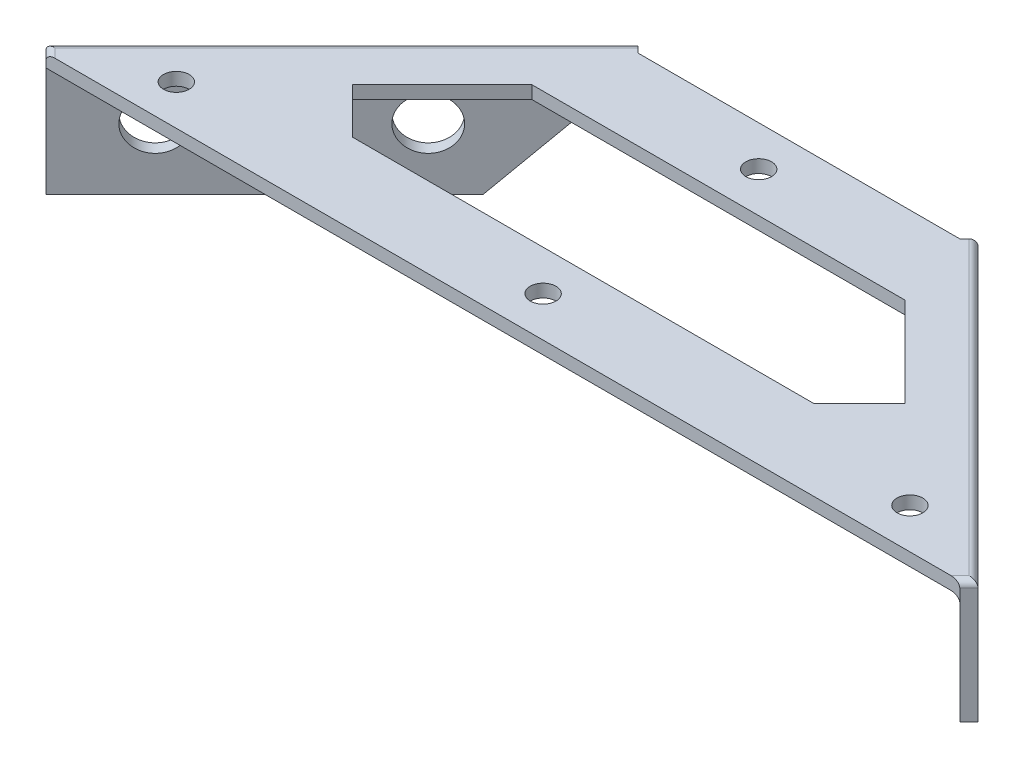
SolidWorks part; units mm, degrees
material "1060 Alloy"
ref_plane "Front Plane" through (0, 0, 0) normal (0, 0, 1) x (1, 0, 0)
ref_plane "Top Plane" through (0, 0, 0) normal (0, 1, 0) x (1, 0, 0)
ref_plane "Right Plane" through (0, 0, 0) normal (1, 0, 0) x (0, 0, -1)
sketch "Sketch1" plane through (0, 0, 0) normal (0, 1, 0) x (1, 0, 0)
  line L0 (0, 0) -> (0, 46) construction
  line L1 (25, 46) -> (-25, 46)
  line L2 (-25, 46) -> (-71, 0)
  line L3 (-71, 0) -> (71, 0)
  line L4 (25, 46) -> (71, 0)
  dimension "D1" = 46
  dimension "D2" = 71
  dimension "D3" = 45
extrude "Boss-Extrude1" add sketch "Sketch1" along normal blind 2
sketch "Sketch2" plane through (0, 0, 0) normal (0, -1, 0) x (-1, 0, 0)
  line L0 (25, 46) -> (71, 0)
  line L1 (25, 46) -> (26.4142, 47.4142)
  line L2 (71, 0) -> (72.4142, 1.4142)
  line L3 (26.4142, 47.4142) -> (72.4142, 1.4142)
  line L4 (0, 46) -> (0, 0) construction
  line L5 (-25, 46) -> (25, 46) construction
  line L6 (-26.4142, 47.4142) -> (-72.4142, 1.4142)
  line L7 (-71, 0) -> (-72.4142, 1.4142)
  line L8 (-25, 46) -> (-26.4142, 47.4142)
  line L9 (-25, 46) -> (-71, 0)
  dimension "D1" = 2
extrude "Boss-Extrude2" add sketch "Sketch2" along normal blind 17 and the other way up to surface other way up to face at (0, 2, -23)
sketch "Sketch7" plane through (-36.9142, 0, -36.9142) normal (-0.7071, 0, -0.7071) x (-0.7071, 0, 0.7071)
  line L0 (50.2046, -7.5) -> (-14.8492, -7.5) construction
  line L1 (50.2046, 2) -> (50.2046, -17) construction
  line L2 (-14.8492, 2) -> (-14.8492, -17) construction
  circle A0 centre (38.2046, -7.5) radius 4
  circle A1 centre (8.2046, -7.5) radius 4
  point P10 (37.801, -7.5)
  point P11 (38.8861, -7.5)
  dimension "D1" = 8
  dimension "D2" = 30
  dimension "D3" = 12
extrude "Cut-Extrude4" cut sketch "Sketch7" against normal through all
fillet "Fillet1" radius 1 5 edges at (71.7071, 2, -0.7071) (-71.7071, 2, -0.7071) (-49.4142, 2, -24.4142) (48, 0, -23) (49.4142, 2, -24.4142)
sketch "Sketch3" plane through (-35.5, 0, -35.5) normal (0.7071, 0, 0.7071) x (0.7071, 0, -0.7071)
  line L0 (14.8492, 0) -> (-2.1508, -17)
  line L1 (14.8492, -17) -> (-50.2046, -17) construction
  line L2 (-2.1508, -17) -> (14.8492, -17)
  line L3 (14.8492, -17) -> (14.8492, 0)
  dimension "D1" = 45
extrude "Cut-Extrude1" cut sketch "Sketch3" against normal through all
ref_plane "Plane1" through (0, 0, 0) normal (-1, 0, 0) x (0, 0, 1)
sketch "Sketch4" plane through (0, 0, 0) normal (0, -1, 0) x (-1, 0, 0)
  line L0 (0, 46.3421) -> (0, 0) construction
  line L1 (0, -9.9) -> (0, 9.9) construction
  line L3 (29.0147, 33.5) -> (-29.0147, 33.5)
  line L4 (0, 33.5) -> (0, 12.5)
  line L5 (-35.8726, 12.5) -> (35.8726, 12.5)
  line L7 (71, 0) -> (-69.5858, 0) construction
  line L8 (35.8726, 12.5) -> (42.9437, 19.5711)
  line L9 (42.9437, 19.5711) -> (29.0147, 33.5)
  line L10 (25, 46) -> (71, 0) construction
  line L11 (37.0208, 33.9792) -> (71, 0) construction
  line L12 (-42.9437, 19.5711) -> (-29.0147, 33.5)
  line L13 (-35.8726, 12.5) -> (-42.9437, 19.5711)
  point P16 (40.6456, 23.2833)
  dimension "D1" = 12.5
  dimension "D2" = 21
  dimension "D3" = 135
  dimension "D4" = 6
  dimension "D5" = 10
extrude "Cut-Extrude2" cut sketch "Sketch4" against normal through all contours L8 L9 L3 L4 L5 | L13 L5 L4 L3 L12
mirror "Mirror1" about plane through (0, 0, 0) normal (-1, 0, 0) of "Cut-Extrude4", "Cut-Extrude1"
sketch "Sketch5" plane through (0, 0, 0) normal (0, -1, 0) x (-1, 0, 0)
  line L0 (0, 0) -> (0, 12.5) construction
  line L1 (0, -9.9) -> (0, 9.9) construction
  line L2 (-35.8726, 12.5) -> (35.8726, 12.5) construction
  line L3 (0, 33.5) -> (0, 46) construction
  line L4 (29.0147, 33.5) -> (-29.0147, 33.5) construction
  line L5 (-23.5858, 46) -> (25, 46) construction
  line L6 (0, 6.25) -> (-63.3358, 6.25) construction
  line L7 (-23.5858, 46) -> (-69.5858, 0) construction
  circle A0 centre (0, 6.25) radius 2
  circle A1 centre (0, 39.75) radius 2
  circle A2 centre (-57, 6.25) radius 2
  circle A3 centre (57, 6.25) radius 2
  dimension "D1" = 4
  dimension "D2" = 4
  dimension "D3" = 57
extrude "Cut-Extrude3" cut sketch "Sketch5" against normal through all
